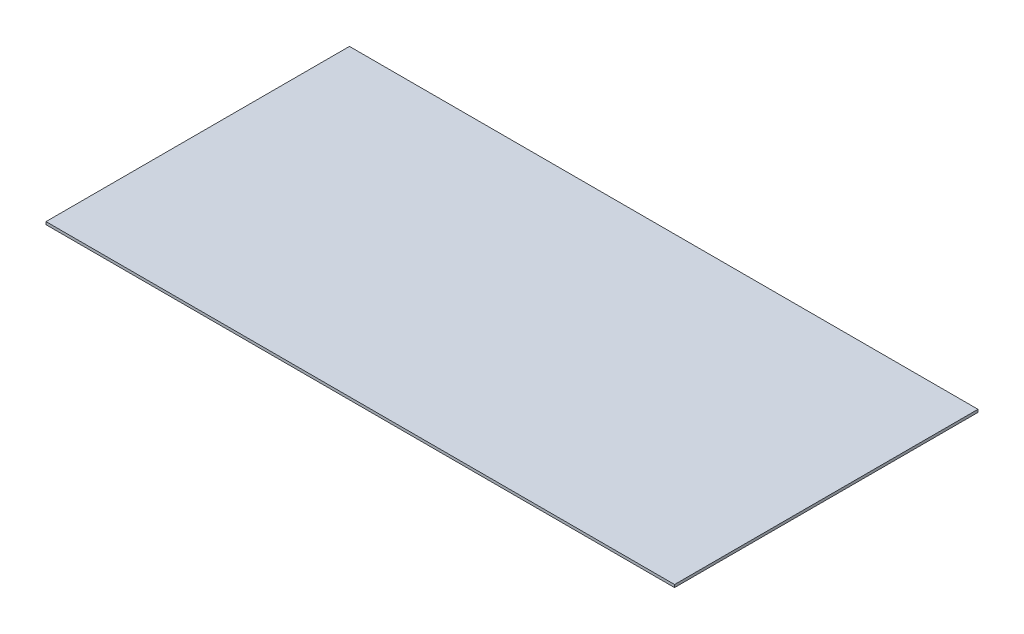
SolidWorks part; units mm, degrees
material "ABS PC"
ref_plane "Front Plane" through (0, 0, 0) normal (0, 0, 1) x (1, 0, 0)
ref_plane "Top Plane" through (0, 0, 0) normal (0, 1, 0) x (1, 0, 0)
ref_plane "Right Plane" through (0, 0, 0) normal (1, 0, 0) x (0, 0, -1)
sketch "Sketch1" plane through (0, 0, 0) normal (0, 1, 0) x (1, 0, 0)
  line L1 (0, 0) -> (736.6, 0)
  line L2 (0, 0) -> (0, 355.6)
  line L3 (0, 355.6) -> (736.6, 355.6)
  line L4 (736.6, 0) -> (736.6, 355.6)
  dimension "D1" = 736.6
  dimension "D2" = 355.6
extrude "Boss-Extrude1" add sketch "Sketch1" along normal blind 3.175
